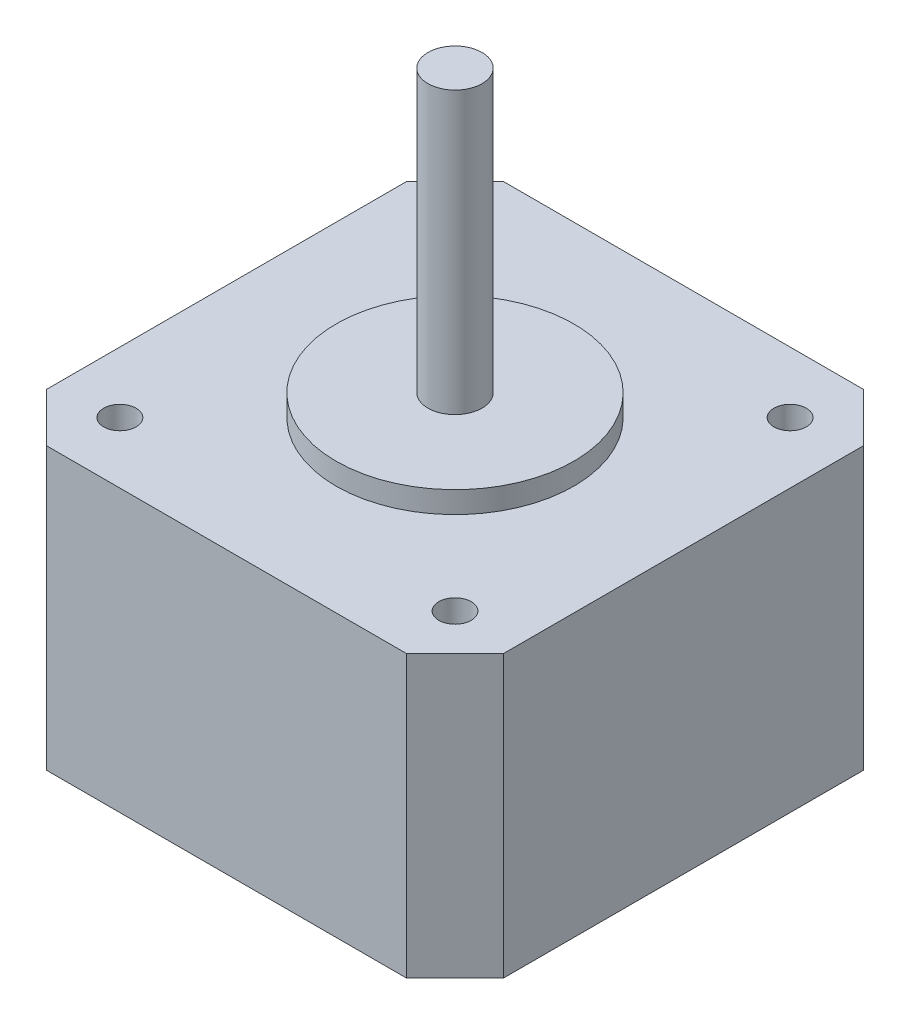
SolidWorks part; units mm, degrees
ref_plane "Ebene vorne" through (0, 0, 0) normal (0, 0, 1) x (1, 0, 0)
ref_plane "Ebene oben" through (0, 0, 0) normal (0, 1, 0) x (1, 0, 0)
ref_plane "Ebene rechts" through (0, 0, 0) normal (1, 0, 0) x (0, 0, -1)
sketch "Skizze1" plane through (0, 0, 0) normal (0, 1, 0) x (1, 0, 0)
  line L0 (0, 37.8) -> (4.5, 42.3)
  line L1 (4.5, 0) -> (37.8, 0)
  line L2 (0, 4.5) -> (0, 37.8)
  line L3 (4.5, 42.3) -> (37.8, 42.3)
  line L4 (42.3, 4.5) -> (42.3, 37.8)
  line L5 (37.8, 42.3) -> (42.3, 37.8)
  line L6 (37.8, 0) -> (42.3, 4.5)
  line L7 (0, 4.5) -> (4.5, 0)
  point P0 (0, 0)
  point P1 (42.3, 42.3)
  point P2 (0, 42.3)
  point P3 (42.3, 0)
  dimension "D1" = 42.3
  dimension "D2" = 42.3
extrude "Aufsatz-Linear austragen1" add sketch "Skizze1" along normal blind 26
sketch "Skizze2" plane through (0, 26, 0) normal (0, 1, 0) x (1, 0, 0)
  line L0 (21.15, 44.2844) -> (21.15, -12.2448) construction
  line L1 (-25.3803, 21.15) -> (67.7626, 21.15) construction
  line L2 (37.8, 42.3) -> (4.5, 42.3) construction
  line L3 (4.5, 0) -> (37.8, 0) construction
  line L4 (0, 37.8) -> (0, 4.5) construction
  line L5 (42.3, 4.5) -> (42.3, 37.8) construction
  circle A0 centre (21.15, 21.15) radius 11
  dimension "D1" = 22
extrude "Aufsatz-Linear austragen2" add sketch "Skizze2" along normal blind 2
sketch "Skizze3" plane through (0, 28, 0) normal (0, 1, 0) x (1, 0, 0)
  circle A0 centre (21.15, 21.15) radius 2.5
  circle A1 centre (21.15, 21.15) radius 11 construction
  dimension "D1" = 5
extrude "Aufsatz-Linear austragen3" add sketch "Skizze3" along normal blind 26
sketch "Skizze4" plane through (0, 26, 0) normal (0, 1, 0) x (1, 0, 0)
  line L0 (21.15, -2.4213) -> (21.15, 44.205) construction
  line L1 (-4.6255, 21.15) -> (49.1893, 21.15) construction
  line L2 (37.8, 42.3) -> (4.5, 42.3) construction
  line L3 (4.5, 0) -> (37.8, 0) construction
  line L4 (0, 37.8) -> (0, 4.5) construction
  line L5 (42.3, 4.5) -> (42.3, 37.8) construction
  circle A0 centre (5.65, 36.65) radius 1.5
  circle A1 centre (36.65, 36.65) radius 1.5
  circle A2 centre (5.65, 5.65) radius 1.5
  circle A3 centre (36.65, 5.65) radius 1.5
  dimension "D2" = 3
  dimension "D3" = 3
  dimension "D1" = 15.5
  dimension "D4" = 31
extrude "Schnitt-Linear austragen1" cut sketch "Skizze4" against normal blind 4.5
